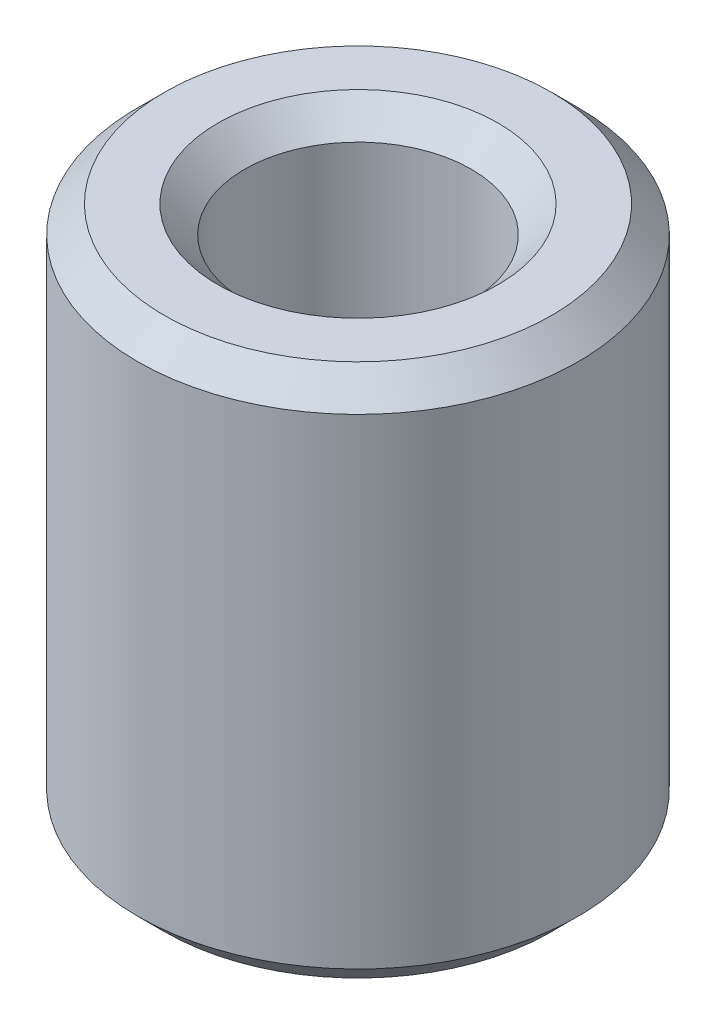
SolidWorks part; units mm, degrees
material "1060 Alloy"
ref_plane "Спереди" through (0, 0, 0) normal (0, 0, 1) x (1, 0, 0)
ref_plane "Сверху" through (0, 0, 0) normal (0, 1, 0) x (1, 0, 0)
ref_plane "Справа" through (0, 0, 0) normal (1, 0, 0) x (0, 0, -1)
sketch "Sketch1" plane through (0, 0, 0) normal (1, 0, 0) x (0, 0, -1)
  line L0 (0, 0) -> (0, 20) construction
  line L1 (0, 20) -> (-4.25, 20) construction
  line L2 (-4.25, 20) -> (-4.25, 12)
  line L3 (-2.75, 0) -> (0, 0) construction
  line L4 (-4.25, 12) -> (-2.75, 8)
  line L5 (-2.75, 8) -> (-2.75, 0)
  line L6 (-2.75, 0) -> (-8.25, 0)
  line L7 (-8.25, 0) -> (-8.25, 20)
  line L8 (-8.25, 20) -> (-4.25, 20)
  dimension "D1" = 2.75
  dimension "D2" = 4.25
  dimension "D3" = 4
  dimension "D4" = 8
  dimension "D5" = 8
  dimension "D6" = 20
revolve "Revolve1" add sketch "Sketch1" angle 360 about L0
chamfer "Chamfer1" distance 1 angle 45 4 edges at (0, 0, -8.25) (0, 0, -2.75) (0, 20, -8.25) (0, 20, -4.25)
